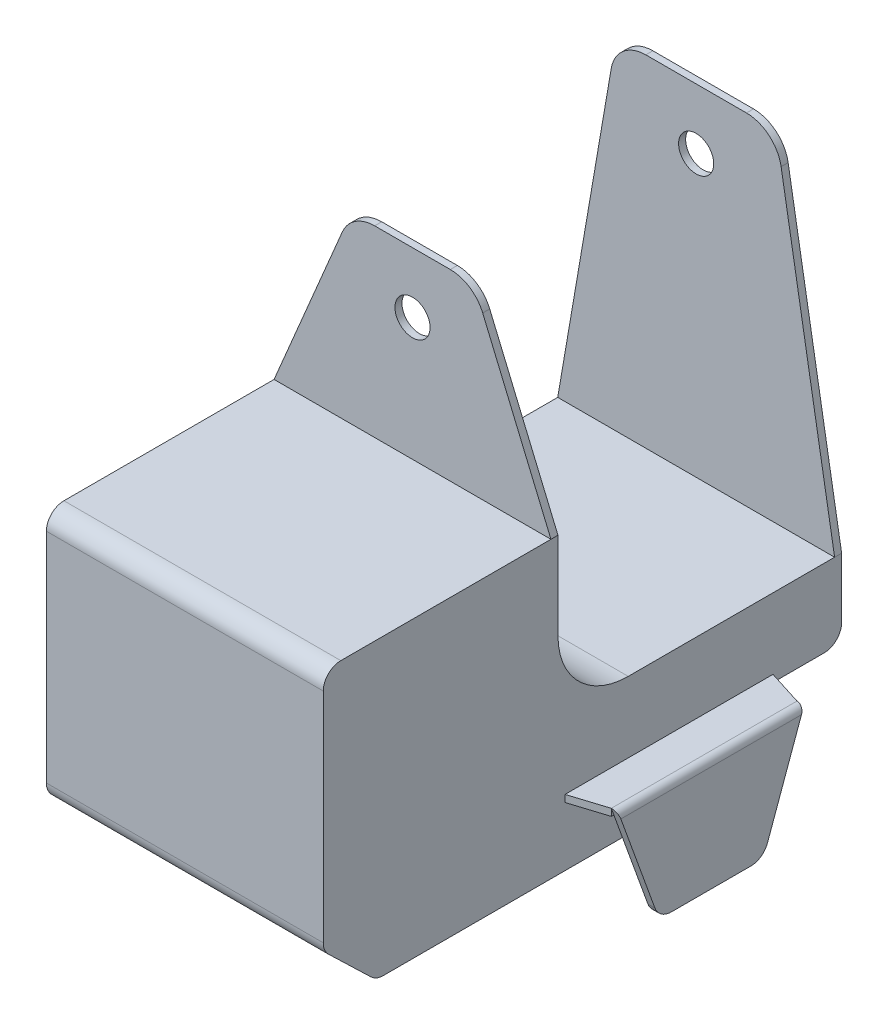
SolidWorks part; units mm, degrees
ref_plane "Front Plane" through (0, 0, 0) normal (0, 0, 1) x (1, 0, 0)
ref_plane "Top Plane" through (0, 0, 0) normal (0, 1, 0) x (1, 0, 0)
ref_plane "Right Plane" through (0, 0, 0) normal (1, 0, 0) x (0, 0, -1)
sketch "Sketch2" plane through (0, 0, 0) normal (1, 0, 0) x (0, 0, -1)
  line L0 (73.765, -25.6492) -> (47.665, -25.6492)
  line L1 (-73.765, 41.2308) -> (-6.965, 41.2308)
  line L2 (-73.765, 41.2308) -> (-73.765, -27.9492)
  line L3 (-58.695, -42.4492) -> (47.665, -42.4492)
  line L4 (73.765, -3.5514) -> (73.765, -25.6492)
  line L5 (47.665, -25.6492) -> (47.665, -42.4492)
  line L6 (-6.965, 41.2308) -> (-6.965, 16.4486)
  line L7 (13.035, -3.5514) -> (73.765, -3.5514)
  line L8 (-73.765, -27.9492) -> (-58.695, -42.4492)
  arc A0 (13.035, -3.5514) -> (-6.965, 16.4486) centre (13.035, 16.4486) cw
  point P12 (-6.965, -3.5514)
  dimension "D6" = 20
  dimension "D2" = 16.8
  dimension "D3" = 26.1
  dimension "D5" = 80.73
extrude "Boss-Extrude1" add sketch "Sketch2" along normal blind 78.8
sketch "Sketch4" plane through (0, 0, -73.765) normal (0, 0, -1) x (-1, 0, 0)
  line L0 (-78.8, -3.5514) -> (0, -3.5514)
  line L1 (0, -3.5514) -> (-16.65, 93.4086)
  line L2 (-16.65, 93.4086) -> (-62.15, 93.4086)
  line L3 (-62.15, 93.4086) -> (-78.8, -3.5514)
  dimension "D1" = 45.5
  dimension "D2" = 96.96
extrude "Boss-Extrude2" add sketch "Sketch4" against normal blind 2
fillet "Fillet2" radius 10 2 edges at (16.65, 93.4086, -72.765) (62.15, 93.4086, -72.765)
sketch "Sketch5" plane through (0, 0, 6.965) normal (0, 0, -1) x (-1, 0, 0)
  line L0 (-78.8, 41.2308) -> (0, 41.2308)
  line L1 (0, 41.2308) -> (-22, 93.4086)
  line L2 (-22, 93.4086) -> (-56.8, 93.4086)
  line L3 (-56.8, 93.4086) -> (-78.8, 41.2308)
  dimension "D1" = 34.8
extrude "Boss-Extrude3" add sketch "Sketch5" against normal blind 2
fillet "Fillet3" radius 10 2 edges at (56.8, 93.4086, 7.965) (22, 93.4086, 7.965)
fillet "Fillet6" radius 5 5 edges at (39.4, 41.2308, 73.765) (39.4, -27.9492, 73.765) (39.4, -42.4492, 58.695) (39.4, -42.4492, -47.665) (39.4, -25.6492, -73.765)
sketch "Sketch6" plane through (0, 0, -73.765) normal (0, 0, -1) x (-1, 0, 0)
  line L0 (-65.1036, 76.2086) -> (-13.6964, 76.2086) construction
  line L1 (-63.5766, 85.101) -> (-78.8, -3.5514) construction
  line L2 (0, -3.5514) -> (-15.2234, 85.101) construction
  line L3 (-28.6362, 93.4086) -> (-50.1638, 93.4086) construction
  circle A0 centre (-39.4, 76.2086) radius 5
  point P6 (-39.4, 93.4086)
  dimension "D1" = 17.2
extrude "Cut-Extrude1" cut sketch "Sketch6" against normal up to surface (82.73 mm away) up to face at (42.7297, 74.4409, 8.965)
sketch "Sketch7" plane through (78.8, 0, 0) normal (1, 0, 0) x (0, 0, -1)
  line L0 (54.225, -25.6492) -> (47.665, -25.6492)
  line L1 (47.665, -25.6492) -> (68.765, -25.6492) construction
  line L2 (47.665, -25.6492) -> (-4.955, -25.6492)
  line L3 (-4.955, -25.6492) -> (-4.955, -23.6492)
  line L4 (-4.955, -23.6492) -> (54.225, -23.6492)
  line L5 (54.225, -23.6492) -> (54.225, -25.6492)
  dimension "D1" = 6.56
  dimension "D2" = 59.18
  dimension "D3" = 2
extrude "Boss-Extrude4" add sketch "Sketch7" along normal blind 10
sketch "Sketch9" plane through (0, -23.6492, 0) normal (0, 1, 0) x (1, 0, 0)
  line L1 (88.8, 54.225) -> (88.8, -4.955) construction
  line L4 (88.8, 51.06) -> (78.8, 54.225)
  line L5 (78.8, 54.225) -> (88.8, 54.225)
  line L6 (88.8, 54.225) -> (88.8, 51.06)
  line L7 (88.8, -1.79) -> (78.8, -4.955)
  line L8 (78.8, -4.955) -> (88.8, -4.955)
  line L9 (88.8, -4.955) -> (88.8, -1.79)
  dimension "D1" = 52.85
extrude "Cut-Extrude2" cut sketch "Sketch9" against normal up to next
sketch "Sketch10" plane through (88.8, 0, 0) normal (1, 0, 0) x (0, 0, -1)
  line L1 (-1.79, -23.6492) -> (51.06, -23.6492)
  line L2 (-1.79, -23.6492) -> (-1.79, -25.6492)
  line L3 (-1.79, -25.6492) -> (51.06, -25.6492)
  line L4 (51.06, -23.6492) -> (51.06, -25.6492)
extrude "Boss-Extrude5" add sketch "Sketch10" along normal blind 2
sketch "Sketch11" plane through (0, -25.6492, 0) normal (0, -1, 0) x (1, 0, 0)
  line L1 (88.8, 1.79) -> (90.8, 1.79)
  line L2 (88.8, 1.79) -> (88.8, -51.06)
  line L3 (88.8, -51.06) -> (90.8, -51.06)
  line L4 (90.8, 1.79) -> (90.8, -51.06)
extrude "Boss-Extrude6" add sketch "Sketch11" along normal blind 30.1
sketch "Sketch12" plane through (90.8, 0, 0) normal (1, 0, 0) x (0, 0, -1)
  line L2 (51.06, -55.7492) -> (-1.79, -55.7492) construction
  line L4 (9.82, -55.7492) -> (-1.79, -23.6492)
  line L5 (-1.79, -23.6492) -> (-1.79, -55.7492)
  line L6 (-1.79, -55.7492) -> (9.82, -55.7492)
  line L7 (39.45, -55.7492) -> (51.06, -23.6492)
  line L8 (51.06, -23.6492) -> (51.06, -55.7492)
  line L9 (51.06, -55.7492) -> (39.45, -55.7492)
  dimension "D1" = 29.63
extrude "Cut-Extrude3" cut sketch "Sketch12" against normal up to surface (2 mm away) up to face at (88.8, -40.6992, -24.635)
fillet "Fillet9" radius 5 2 edges at (89.8, -55.7492, -39.45) (89.8, -55.7492, -9.82)
fillet "Fillet11" radius 2 1 edges at (90.8, -23.6492, -24.635)
sketch "Sketch13" plane through (0, -42.4492, 0) normal (0, -1, 0) x (1, 0, 0)
  line L0 (0, -24.265) -> (78.8, -24.265) construction
  line L1 (0, 56.6802) -> (0, -42.665) construction
  line L2 (78.8, 56.6802) -> (78.8, -42.665) construction
  line L3 (78.8, -73.765) -> (0, -73.765) construction
  circle A0 centre (39.4, -24.265) radius 4.9
  dimension "D1" = 49.5
extrude "Boss-Extrude7" add sketch "Sketch13" along normal blind 10
